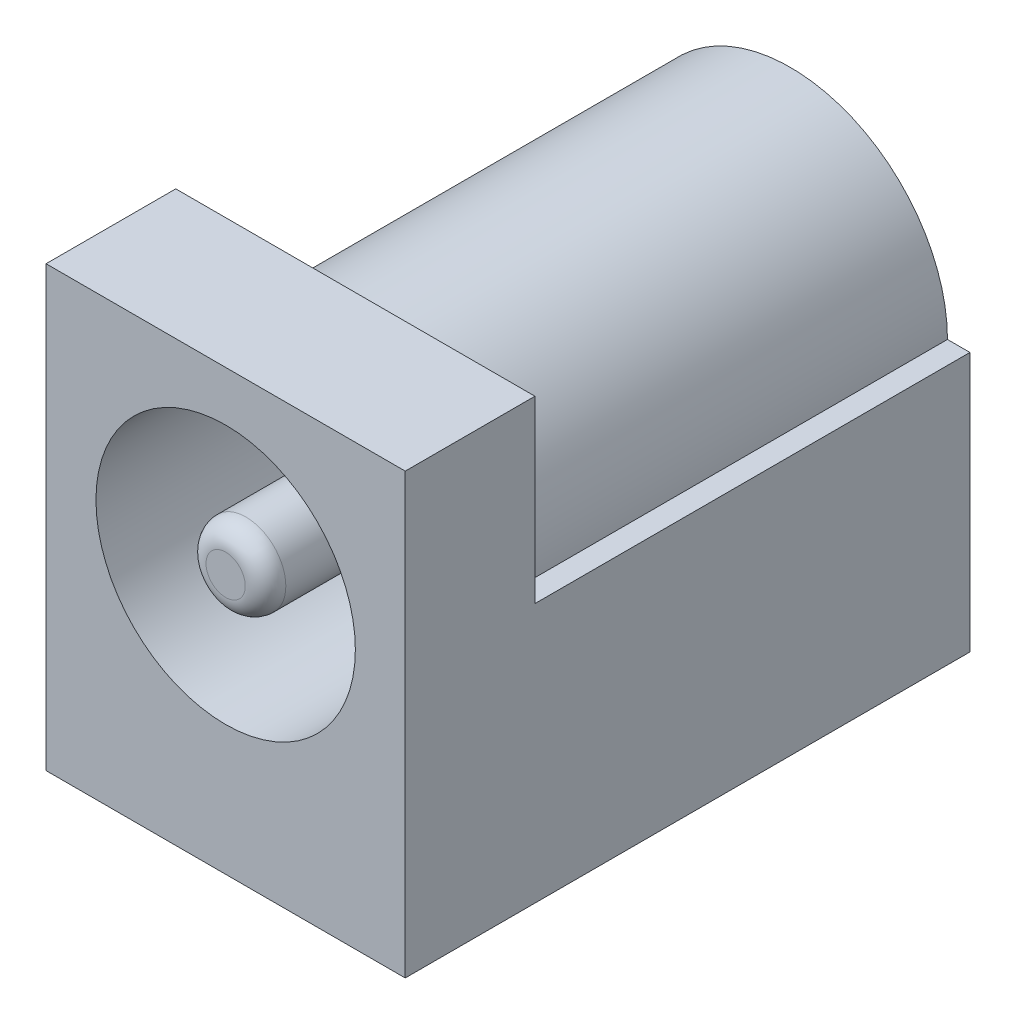
SolidWorks part; units mm, degrees
ref_plane "Front Plane" through (0, 0, 0) normal (0, 0, 1) x (1, 0, 0)
ref_plane "Top Plane" through (0, 0, 0) normal (0, 1, 0) x (1, 0, 0)
ref_plane "Right Plane" through (0, 0, 0) normal (1, 0, 0) x (0, 0, -1)
sketch "Sketch2" plane through (0, 0, 0) normal (0, 0, 1) x (1, 0, 0)
  line L1 (-4.5, -5.5) -> (4.5, -5.5)
  line L2 (-4.5, -5.5) -> (-4.5, 5.5)
  line L3 (-4.5, 5.5) -> (4.5, 5.5)
  line L4 (4.5, -5.5) -> (4.5, 5.5)
  line L5 (-4.5, -5.5) -> (4.5, 5.5) construction
  line L6 (-4.5, 5.5) -> (4.5, -5.5) construction
  point P0 (0, 0)
  dimension "D1" = 11
  dimension "D2" = 9
extrude "Boss-Extrude1" add sketch "Sketch2" along normal blind 3.25
sketch "Sketch3" plane through (0, 0, 0) normal (0, 0, -1) x (-1, 0, 0)
  line L0 (4.5, -5.5) -> (-4.5, -5.5) construction
  line L1 (-4.5, -5.5) -> (-4.5, 5.5) construction
  line L2 (-4.5, 1) -> (-3.937, 1)
  line L3 (-4.5, 1) -> (-4.5, -5.5)
  line L4 (-4.5, -5.5) -> (4.5, -5.5)
  line L5 (4.5, 1) -> (4.5, -5.5)
  line L6 (3.937, 1) -> (4.5, 1)
  arc A0 (3.937, 1) -> (-3.937, 1) centre (0, 1) ccw
  dimension "D1" = 7.874
  dimension "D2" = 6.5
extrude "Boss-Extrude2" add sketch "Sketch3" along normal blind 10.9
sketch "Sketch4" plane through (0, 0, 3.25) normal (0, 0, 1) x (1, 0, 0)
  line L0 (-4.5, -5.5) -> (4.5, -5.5) construction
  circle A0 centre (0, 1) radius 3.25
  circle A1 centre (0, 1) radius 1
  dimension "D1" = 6.5
  dimension "D3" = 2
  dimension "D2" = 6.5
extrude "Cut-Extrude1" cut sketch "Sketch4" against normal blind 10.9
fillet "Fillet1" radius 0.508 1 edges at (1, 1, 3.25)
